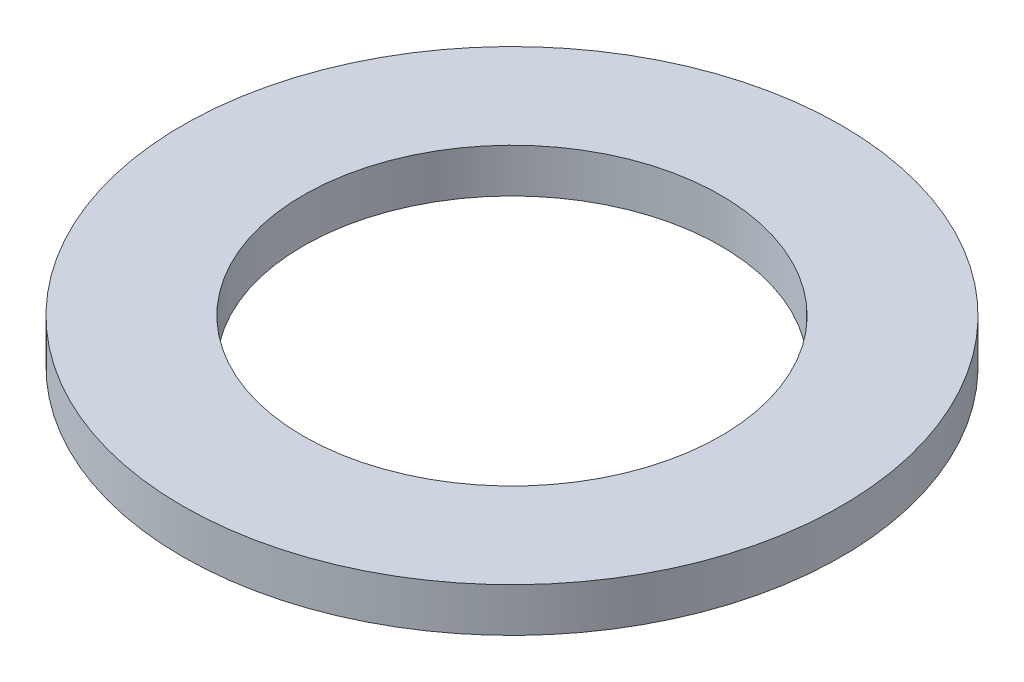
SolidWorks part; units mm, degrees
ref_plane "Front Plane" through (0, 0, 0) normal (0, 0, 1) x (1, 0, 0)
ref_plane "Top Plane" through (0, 0, 0) normal (0, 1, 0) x (1, 0, 0)
ref_plane "Right Plane" through (0, 0, 0) normal (1, 0, 0) x (0, 0, -1)
sketch "Sketch1" plane through (0, 0, 0) normal (0, 1, 0) x (1, 0, 0)
  circle A0 centre (0, 0) radius 9.5
  circle A1 centre (0, 0) radius 15
  dimension "D1" = 19
  dimension "D2" = 30
extrude "Boss-Extrude1" add sketch "Sketch1" along normal blind 2
